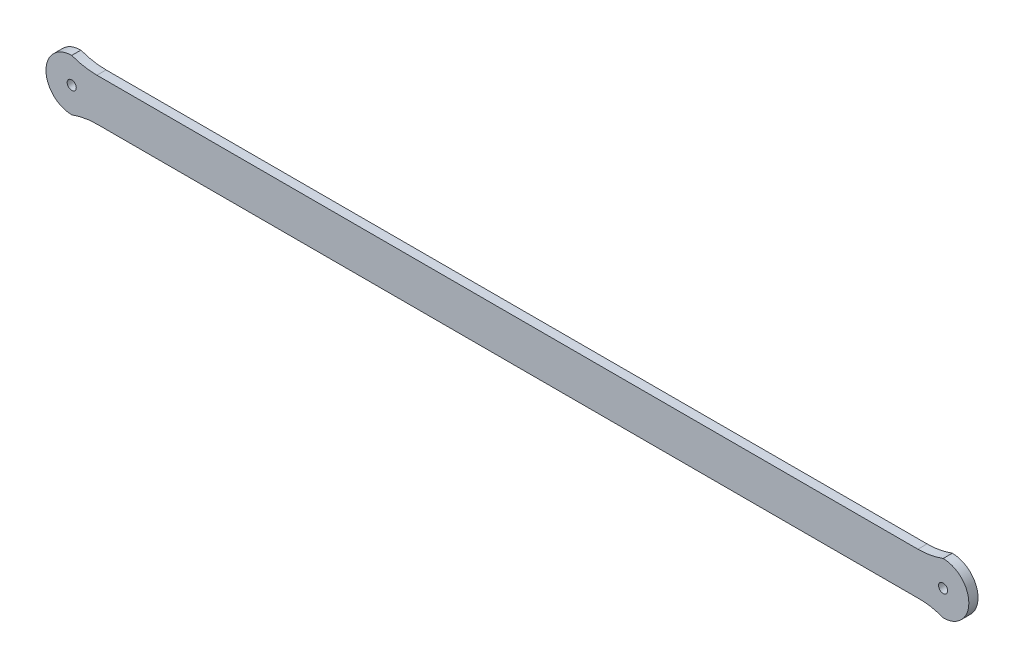
SolidWorks part; units mm, degrees
ref_plane "Front Plane" through (0, 0, 0) normal (0, 0, 1) x (1, 0, 0)
ref_plane "Top Plane" through (0, 0, 0) normal (0, 1, 0) x (1, 0, 0)
ref_plane "Right Plane" through (0, 0, 0) normal (1, 0, 0) x (0, 0, -1)
sketch "Sketch1" plane through (0, 0, 0) normal (0, 0, 1) x (1, 0, 0)
  line L0 (-143.2741, 7.39) -> (143.2741, 7.39)
  line L1 (-143.272, -7.39) -> (143.272, -7.39)
  line L2 (0, 7.39) -> (0, -7.39) construction
  circle A0 centre (-152.07, 0) radius 1.5875
  circle A1 centre (152.07, 0) radius 1.5875
  arc A2 (-152.07, 8.978) -> (-152.07, -8.978) centre (-152.07, 0) ccw
  arc A3 (152.07, -8.978) -> (152.07, 8.978) centre (152.07, 0) ccw
  arc A4 (-152.07, 8.978) -> (-143.2741, 7.39) centre (-143.2741, 32.5441) ccw
  arc A5 (143.2741, 7.39) -> (152.07, 8.978) centre (143.2467, 32.6958) ccw
  arc A6 (-143.272, -7.39) -> (-152.07, -8.978) centre (-143.1295, -33.3454) ccw
  arc A7 (152.07, -8.978) -> (143.272, -7.39) centre (143.9608, -28.7397) ccw
extrude "Boss-Extrude1" add sketch "Sketch1" along normal mid plane 3.2
